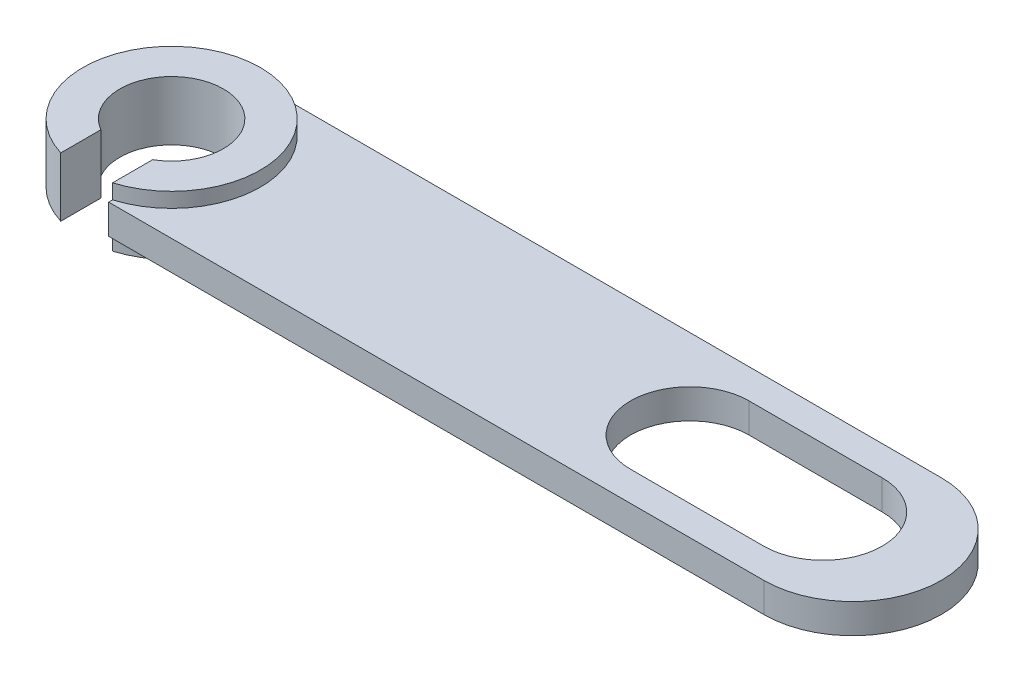
SolidWorks part; units mm, degrees
material "ABS PC"
ref_plane "Piano frontale" through (0, 0, 0) normal (0, 0, 1) x (1, 0, 0)
ref_plane "Piano superiore" through (0, 0, 0) normal (0, 1, 0) x (1, 0, 0)
ref_plane "Piano destro" through (0, 0, 0) normal (1, 0, 0) x (0, 0, -1)
sketch "Schizzo1" plane through (0, 0, 0) normal (0, 1, 0) x (1, 0, 0)
  line L0 (-11.5, 0) -> (11.5, 0) construction
  line L1 (-11.5, 3) -> (11.5, 3)
  line L2 (-11.5, -3) -> (11.5, -3)
  line L3 (10.5, 0) -> (6, 0) construction
  line L4 (10.5, -2) -> (6, -2)
  line L5 (10.5, 2) -> (6, 2)
  line L6 (-11.5, 0) -> (-11.5, -3) construction
  arc A0 (-11.5, 3) -> (-11.5, -3) centre (-11.5, 0) ccw
  arc A1 (11.5, -3) -> (11.5, 3) centre (11.5, 0) ccw
  arc A2 (10.5, -2) -> (10.5, 2) centre (10.5, 0) ccw
  arc A3 (6, 2) -> (6, -2) centre (6, 0) ccw
  circle A4 centre (-11.5, 0) radius 1.75
  point P2 (0, 0)
  point P8 (-14.5, 0)
  point P9 (14.5, 0)
  point P12 (8.25, 0)
  point P19 (12.5, 0)
  dimension "D3" = 1
  dimension "D5" = 4.5
  dimension "D6" = 3.5
  dimension "D1" = 29
  dimension "D2" = 6
  dimension "D4" = 2
extrude "Estrusione-Estrusione1" add sketch "Schizzo1" along normal mid plane 1
sketch "Schizzo2" plane through (0, 0, 0) normal (0, 1, 0) x (1, 0, 0)
  line L0 (-11.5, 0) -> (-10.625, -1.5155) construction
  line L2 (-11.5, 0) -> (-12.375, -1.5155) construction
  line L3 (-11.5, 0) -> (-11.5, -3) construction
  line L4 (-10.625, -1.5155) -> (-10.625, -3)
  line L5 (-12.375, -1.5155) -> (-12.375, -2.8696)
  line L6 (-11.5, -3) -> (-13.3746, -3) construction
  line L7 (-11.5, -3) -> (11.5, -3) construction
  line L8 (-11.5, -3) -> (-10.625, -3)
  circle A0 centre (-11.5, 0) radius 1.75 construction
  arc A1 (-12.375, -1.5155) -> (-10.625, -1.5155) centre (-11.5, 0) ccw
  arc A2 (-12.375, -2.8696) -> (-11.5, -3) centre (-11.5, 0) ccw
  arc A3 (-11.5, 3) -> (-11.5, -3) centre (-11.5, 0) ccw construction
  dimension "D1" = 30
  dimension "D2" = 30
extrude "Taglio-Estrusione2" cut sketch "Schizzo2" against normal through all both and the other way through all
sketch "Schizzo4" plane through (0, 0, 0) normal (0, 1, 0) x (1, 0, 0)
  line L0 (-10.625, -3) -> (-10.625, -1.5155) construction
  line L1 (-12.375, -1.5155) -> (-12.375, -2.8696) construction
  line L2 (-10.625, -2.8696) -> (-10.625, -1.5155)
  line L3 (-12.375, -1.5155) -> (-12.375, -2.8696)
  arc A0 (-10.625, -2.8696) -> (-12.375, -2.8696) centre (-11.5, 0) ccw
  arc A1 (-10.625, -1.5155) -> (-12.375, -1.5155) centre (-11.5, 0) ccw construction
  arc A2 (-10.625, -1.5155) -> (-12.375, -1.5155) centre (-11.5, 0) ccw
extrude "Estrusione-Estrusione2" add sketch "Schizzo4" along normal mid plane 2
sketch "Schizzo5" plane through (0, 0, 0) normal (0, 1, 0) x (1, 0, 0)
  line L0 (-11.5, 0) -> (14.5, 0) construction
  arc A0 (11.5, -3) -> (11.5, 3) centre (11.5, 0) ccw construction
